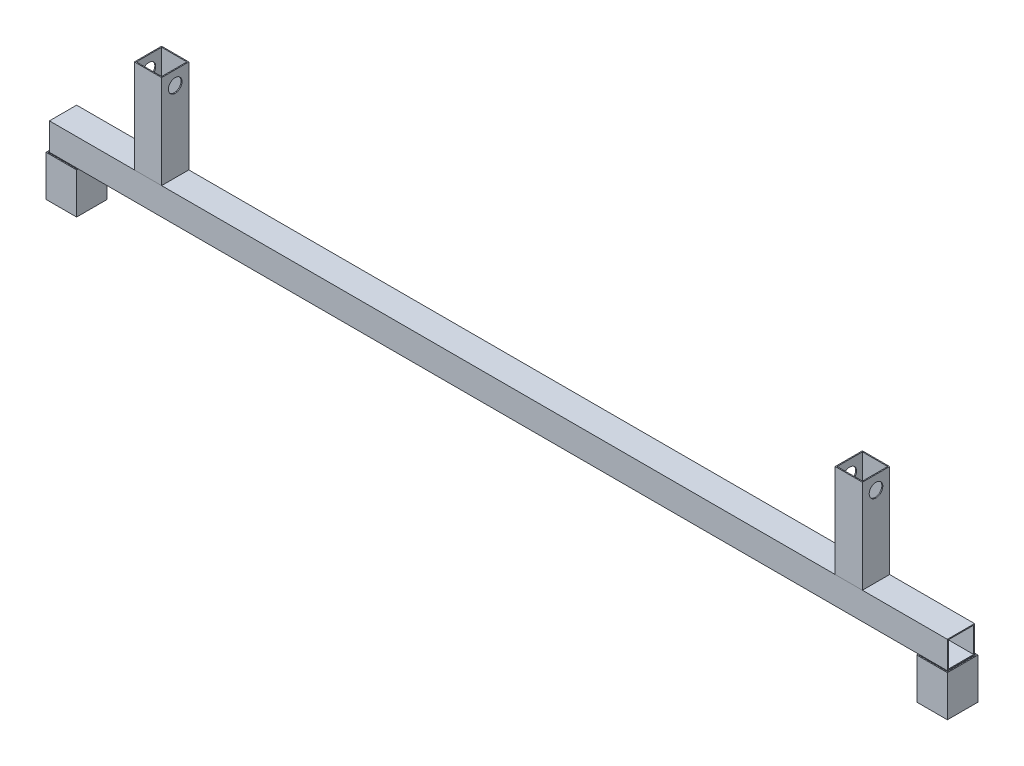
SolidWorks part; units mm, degrees
ref_plane "Alzado" through (0, 0, 0) normal (0, 0, 1) x (1, 0, 0)
ref_plane "Planta" through (0, 0, 0) normal (0, 1, 0) x (1, 0, 0)
ref_plane "Vista lateral" through (0, 0, 0) normal (1, 0, 0) x (0, 0, -1)
sketch "Croquis1" plane through (0, 0, 0) normal (0, 0, 1) x (1, 0, 0)
  line L0 (0, 0) -> (838, 0)
  line L1 (12.7, 0) -> (12.7, -50.8)
  line L2 (825.3, 0) -> (825.3, -50.8)
  line L3 (746, 0) -> (746, 100)
  line L4 (92, 0) -> (92, 100)
  point P13 (12.7, -25.4)
  point P14 (746, 50)
  dimension "D1" = 12.7
  dimension "D2" = 12.7
  dimension "D3" = 100
  dimension "D4" = 92
  dimension "D5" = 50.8
  dimension "D6" = 92
  dimension "D7" = 838
other "Al tube (square) 1 SQ X .035 WALL(1)"
ref_plane "Plano3" through (0, 0, 0) normal (1, 0, 0) x (0, 1, 0)
sketch "Sketch15" plane through (0, 0, 0) normal (1, 0, 0) x (0, 1, 0)
  line L0 (-11.811, -11.811) -> (-11.811, 11.811)
  line L1 (11.811, 11.811) -> (-11.811, 11.811)
  line L2 (11.811, 11.811) -> (11.811, -11.811)
  line L3 (-11.811, -11.811) -> (11.811, -11.811)
  line L4 (-12.7, -12.7) -> (12.7, -12.7)
  line L5 (-12.7, -12.7) -> (-12.7, 12.7)
  line L6 (12.7, 12.7) -> (-12.7, 12.7)
  line L7 (12.7, 12.7) -> (12.7, -12.7)
  line L8 (0, -11.811) -> (0, -12.7) construction
  line L9 (0, -11.811) -> (0, 11.811) construction
  line L10 (0, 11.811) -> (0, 12.7) construction
  line L11 (12.7, 0) -> (11.811, 0) construction
  line L12 (11.811, 0) -> (-11.811, 0) construction
  line L13 (-11.811, 0) -> (-12.7, 0) construction
  point P14 (0, 0)
  dimension "Thickness" = 0.889
  dimension "V_leg" = 25.4
  dimension "H_leg" = 25.4
other "Al tube (square) 1.125 SQ X .035 WALL(2)"
ref_plane "Plano4" through (12.7, 0, 0) normal (0, -1, 0) x (1, 0, 0)
sketch "Sketch16" plane through (12.7, 0, 0) normal (0, -1, 0) x (1, 0, 0)
  line L0 (-13.3985, -13.3985) -> (-13.3985, 13.3985)
  line L1 (13.3985, 13.3985) -> (-13.3985, 13.3985)
  line L2 (13.3985, 13.3985) -> (13.3985, -13.3985)
  line L3 (-13.3985, -13.3985) -> (13.3985, -13.3985)
  line L4 (-14.2875, -14.2875) -> (14.2875, -14.2875)
  line L5 (-14.2875, -14.2875) -> (-14.2875, 14.2875)
  line L6 (14.2875, 14.2875) -> (-14.2875, 14.2875)
  line L7 (14.2875, 14.2875) -> (14.2875, -14.2875)
  line L8 (0, -13.3985) -> (0, -14.2875) construction
  line L9 (0, -13.3985) -> (0, 13.3985) construction
  line L10 (0, 13.3985) -> (0, 14.2875) construction
  line L11 (14.2875, 0) -> (13.3985, 0) construction
  line L12 (13.3985, 0) -> (-13.3985, 0) construction
  line L13 (-13.3985, 0) -> (-14.2875, 0) construction
  point P14 (0, 0)
  dimension "Thickness" = 0.889
  dimension "V_leg" = 28.575
  dimension "H_leg" = 28.575
other "Recortar/Extender1"
sketch "Croquis11" plane through (758.7, 0, 0) normal (1, 0, 0) x (0, 0, -1)
  line L0 (-12.7, 100) -> (12.7, 100) construction
  line L1 (12.7, 100) -> (12.7, 12.7) construction
  circle A0 centre (0, 87.3) radius 6.35
  dimension "D1" = 12.7
  dimension "D2" = 12.7
  dimension "D3" = 12.7
extrude "Cortar-Extruir1" cut sketch "Croquis11" against normal blind 768.858 contours A0
